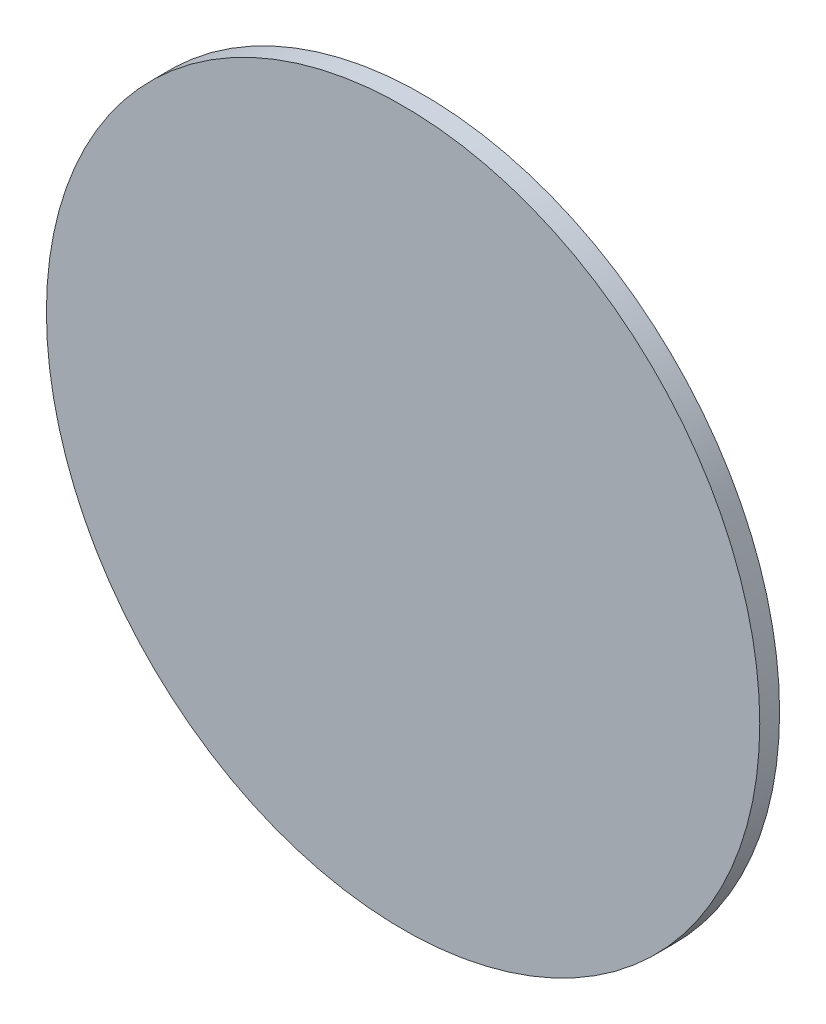
SolidWorks part; units mm, degrees
material "Manual Density from Real Component Motore VTOL - 7in prop"
ref_plane "Piano frontale" through (0, 0, 0) normal (0, 0, 1) x (1, 0, 0)
ref_plane "Piano superiore" through (0, 0, 0) normal (0, 1, 0) x (1, 0, 0)
ref_plane "Piano destro" through (0, 0, 0) normal (1, 0, 0) x (0, 0, -1)
sketch "Schizzo1" plane through (0, 0, 0) normal (0, 0, 1) x (1, 0, 0)
  circle A0 centre (0, 0) radius 90
  dimension "D1" = 180
extrude "Estrusione-Estrusione1" add sketch "Schizzo1" along normal blind 5
